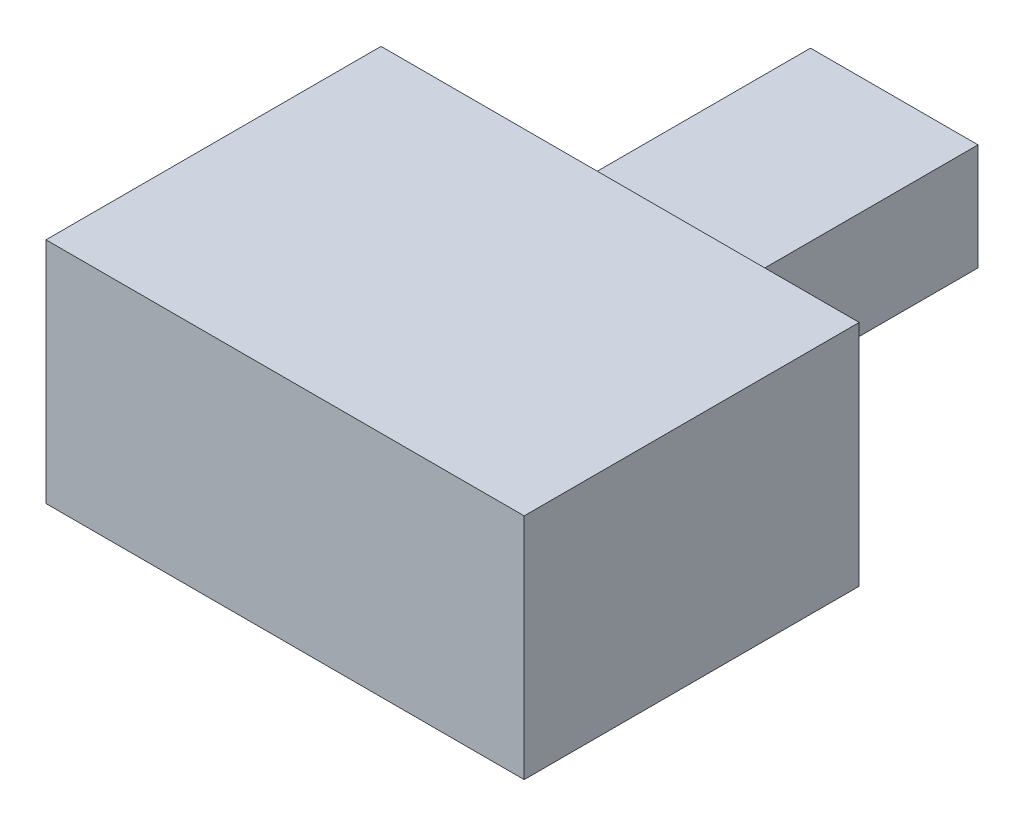
SolidWorks part; units mm, degrees
ref_plane "Front Plane" through (0, 0, 0) normal (0, 0, 1) x (1, 0, 0)
ref_plane "Top Plane" through (0, 0, 0) normal (0, 1, 0) x (1, 0, 0)
ref_plane "Right Plane" through (0, 0, 0) normal (1, 0, 0) x (0, 0, -1)
sketch "Sketch1" plane through (0, 0, 0) normal (0, 0, 1) x (1, 0, 0)
  line L1 (-7.85, -3.75) -> (7.85, -3.75)
  line L2 (-7.85, -3.75) -> (-7.85, 3.75)
  line L3 (-7.85, 3.75) -> (7.85, 3.75)
  line L4 (7.85, -3.75) -> (7.85, 3.75)
  line L5 (-7.85, -3.75) -> (7.85, 3.75) construction
  line L6 (-7.85, 3.75) -> (7.85, -3.75) construction
  point P0 (0, 0)
  dimension "D1" = 15.7
  dimension "D2" = 7.5
extrude "Boss-Extrude1" add sketch "Sketch1" along normal blind 11
sketch "Sketch2" plane through (0, 0, 0) normal (0, 0, -1) x (-1, 0, 0)
  line L1 (-2.75, -1.75) -> (2.75, -1.75)
  line L2 (-2.75, -1.75) -> (-2.75, 1.75)
  line L3 (-2.75, 1.75) -> (2.75, 1.75)
  line L4 (2.75, -1.75) -> (2.75, 1.75)
  line L5 (-2.75, -1.75) -> (2.75, 1.75) construction
  line L6 (-2.75, 1.75) -> (2.75, -1.75) construction
  point P0 (0, 0)
  dimension "D1" = 3.5
  dimension "D2" = 5.5
extrude "Boss-Extrude2" add sketch "Sketch2" along normal blind 9
